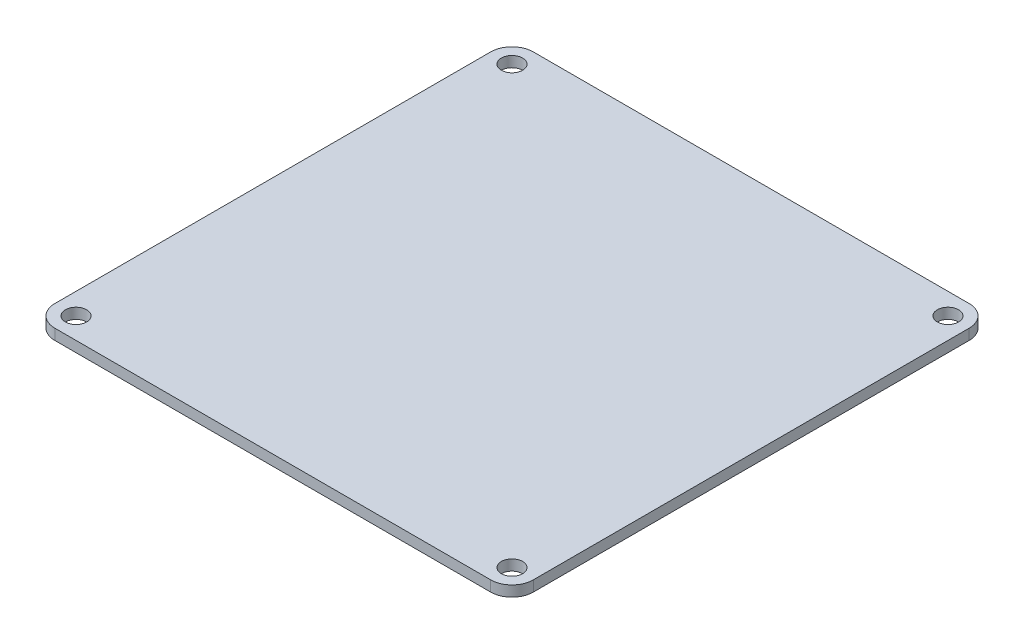
SolidWorks part; units mm, degrees
material "Alloy Steel"
ref_plane "Front Plane" through (0, 0, 0) normal (0, 0, 1) x (1, 0, 0)
ref_plane "Top Plane" through (0, 0, 0) normal (0, 1, 0) x (1, 0, 0)
ref_plane "Right Plane" through (0, 0, 0) normal (1, 0, 0) x (0, 0, -1)
sketch "Sketch2" plane through (0, 0, 0) normal (0, 1, 0) x (1, 0, 0)
  line L1 (-2050, -2250) -> (2050, -2250)
  line L2 (-2250, -2050) -> (-2250, 2050)
  line L3 (-2050, 2250) -> (2050, 2250)
  line L4 (2250, -2050) -> (2250, 2050)
  line L5 (-2250, -2250) -> (2250, 2250) construction
  line L6 (-2250, 2250) -> (2250, -2250) construction
  arc A0 (2250, -2050) -> (2050, -2250) centre (2050, -2050) cw
  arc A1 (-2050, -2250) -> (-2250, -2050) centre (-2050, -2050) cw
  arc A2 (2250, 2050) -> (2050, 2250) centre (2050, 2050) ccw
  arc A3 (-2050, 2250) -> (-2250, 2050) centre (-2050, 2050) ccw
  point P0 (0, 0)
  dimension "D2" = 200
  dimension "D1" = 4500
extrude "Base plate" add sketch "Sketch2" along normal blind 100
sketch "Sketch3" plane through (0, 100, 0) normal (0, 1, 0) x (1, 0, 0)
  line L1 (2050, 2250) -> (-2050, 2250) construction
  line L2 (-2250, 0) -> (2250, 0) construction
  line L3 (2250, -2050) -> (2250, 2050) construction
  line L4 (0, 2250) -> (0, -2250) construction
  line L5 (-2050, -2250) -> (2050, -2250) construction
  line L6 (-2250, 2050) -> (-2250, -2050) construction
  circle A4 centre (-2050, 2050) radius 100
  circle A5 centre (-2050, -2050) radius 100
  circle A6 centre (2050, -2050) radius 100
  circle A7 centre (2050, 2050) radius 100
  point P7 (0, 0)
  dimension "D1" = 200
  dimension "D2" = 200
  dimension "D3" = 200
extrude "base holes" cut sketch "Sketch3" against normal blind 100
